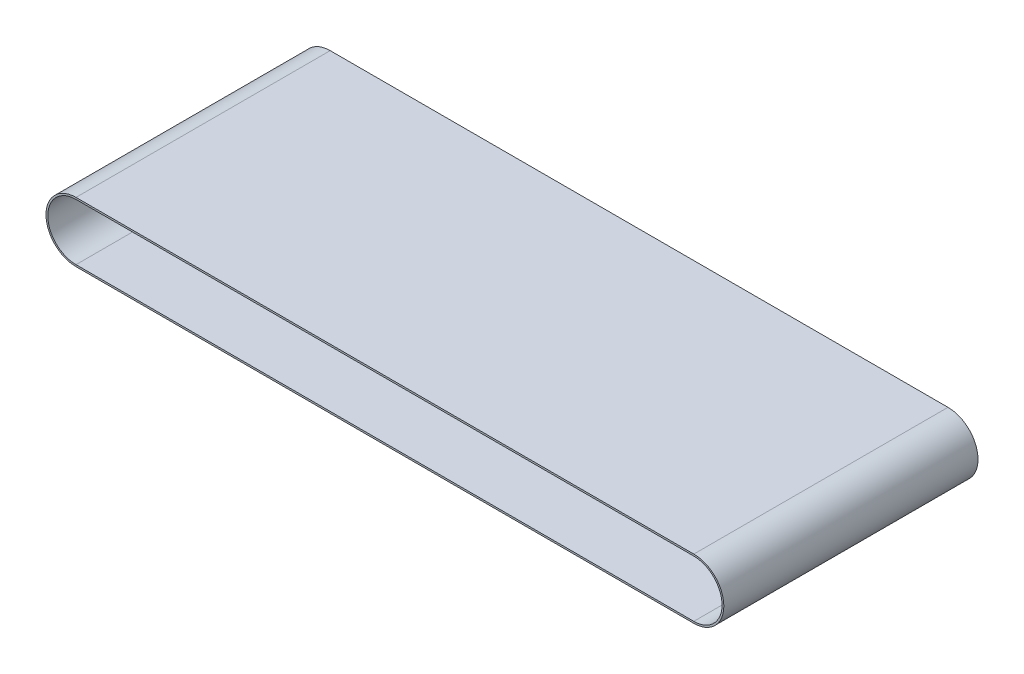
SolidWorks part; units mm, degrees
material "Silicon Rubber"
ref_plane "Front Plane" through (0, 0, 0) normal (0, 0, 1) x (1, 0, 0)
ref_plane "Top Plane" through (0, 0, 0) normal (0, 1, 0) x (1, 0, 0)
ref_plane "Right Plane" through (0, 0, 0) normal (1, 0, 0) x (0, 0, -1)
sketch "Sketch1" plane through (0, 0, 0) normal (0, 0, 1) x (1, 0, 0)
  line L0 (0, 26.9875) -> (555.625, 26.9875)
  line L1 (0, -26.9875) -> (555.625, -26.9875)
  arc A0 (0, 26.9875) -> (0, -26.9875) centre (0, 0) ccw
  arc A1 (555.625, -26.9875) -> (555.625, 26.9875) centre (555.625, 0) ccw
extrude "Boss-Extrude1" add sketch "Sketch1" against normal mid plane 228.6
sketch "Sketch3" plane through (0, 0, 114.3) normal (0, 0, 1) x (1, 0, 0)
  line L0 (0, 25.4) -> (555.625, 25.4)
  line L1 (0, -25.4) -> (555.625, -25.4)
  arc A0 (0, 25.4) -> (0, -25.4) centre (0, 0) ccw
  arc A1 (555.625, -25.4) -> (555.625, 25.4) centre (555.625, 0) ccw
extrude "Cut-Extrude1" cut sketch "Sketch3" against normal through all contours L0 A1 L1 A0
ref_plane "Plane1" through (0, -96.8375, 0) normal (0, -1, 0) x (-1, 0, 0)
